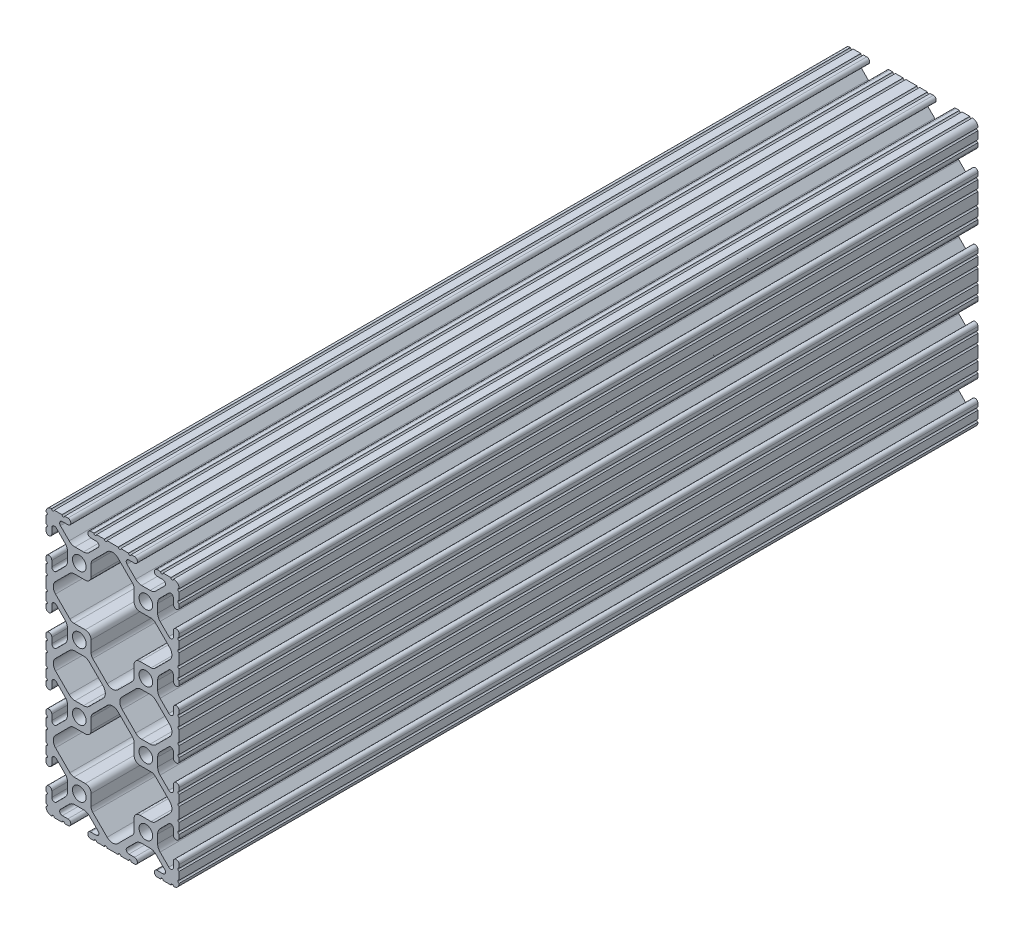
SolidWorks part; units mm, degrees
ref_plane "Front Plane" through (0, 0, 0) normal (0, 0, 1) x (1, 0, 0)
ref_plane "Top Plane" through (0, 0, 0) normal (0, 1, 0) x (1, 0, 0)
ref_plane "Right Plane" through (0, 0, 0) normal (1, 0, 0) x (0, 0, -1)
sketch "Sketch1" plane through (0, 0, 0) normal (0, 0, 1) x (1, 0, 0)
  line L0 (2.286, 55.2958) -> (-2.0184, 55.2958)
  line L1 (-3.5809, 55.943) -> (-9.0725, 61.4345)
  line L2 (-9.0725, 65.5655) -> (-3.5809, 71.057)
  line L3 (-2.0184, 71.7042) -> (2.286, 71.7042)
  line L4 (4.4958, 73.914) -> (4.4958, 78.2184)
  line L5 (5.143, 79.7809) -> (10.6345, 85.2725)
  line L6 (14.7655, 85.2725) -> (20.257, 79.7809)
  line L7 (20.9042, 78.2184) -> (20.9042, 73.914)
  line L8 (23.114, 71.7042) -> (27.4184, 71.7042)
  line L9 (28.9809, 71.057) -> (34.4725, 65.5655)
  line L10 (34.4725, 61.4345) -> (28.9809, 55.943)
  line L11 (27.4184, 55.2958) -> (23.114, 55.2958)
  line L12 (20.9042, 53.086) -> (20.9042, 48.7816)
  line L13 (20.257, 47.2191) -> (14.7655, 41.7275)
  line L14 (10.6345, 41.7275) -> (5.143, 47.2191)
  line L15 (4.4958, 48.7816) -> (4.4958, 53.086)
  line L16 (4.4958, 23.114) -> (4.4958, 27.4184)
  line L17 (5.143, 28.9809) -> (10.6345, 34.4725)
  line L18 (14.7655, 34.4725) -> (20.257, 28.9809)
  line L19 (20.9042, 27.4184) -> (20.9042, 23.114)
  line L20 (23.114, 20.9042) -> (27.4184, 20.9042)
  line L21 (28.9809, 20.257) -> (34.4725, 14.7655)
  line L22 (34.4725, 10.6345) -> (28.9809, 5.143)
  line L23 (27.4184, 4.4958) -> (23.114, 4.4958)
  line L24 (20.9042, 2.286) -> (20.9042, -2.0184)
  line L25 (20.257, -3.5809) -> (14.7655, -9.0725)
  line L26 (10.6345, -9.0725) -> (5.143, -3.5809)
  line L27 (4.4958, -2.0184) -> (4.4958, 2.286)
  line L28 (2.286, 4.4958) -> (-2.0184, 4.4958)
  line L29 (-3.5809, 5.143) -> (-9.0725, 10.6345)
  line L30 (-9.0725, 14.7655) -> (-3.5809, 20.257)
  line L31 (-2.0184, 20.9042) -> (2.286, 20.9042)
  line L32 (27.0186, 29.8958) -> (23.7824, 29.8958)
  line L33 (21.5373, 30.8258) -> (16.3286, 36.0346)
  line L34 (16.3286, 40.1654) -> (21.5373, 45.3742)
  line L35 (23.7824, 46.3042) -> (27.0186, 46.3042)
  line L36 (29.2636, 45.3743) -> (34.4725, 40.1655)
  line L37 (34.4725, 36.0345) -> (29.2636, 30.8257)
  line L38 (1.6176, 29.8958) -> (-1.6186, 29.8958)
  line L39 (-3.8636, 30.8257) -> (-9.0725, 36.0345)
  line L40 (-9.0725, 40.1655) -> (-3.8636, 45.3743)
  line L41 (-1.6186, 46.3042) -> (1.6176, 46.3042)
  line L42 (3.8627, 45.3742) -> (9.0714, 40.1654)
  line L43 (9.0714, 36.0346) -> (3.8627, 30.8258)
  line L44 (-12.7, 40.2336) -> (-12.7, 35.9664)
  line L45 (-12.7, 34.9504) -> (-12.7, 32.004)
  line L46 (-12.7, 30.988) -> (-12.7, 29.7434)
  line L47 (-10.4902, 29.7434) -> (-10.4902, 31.8743)
  line L48 (-8.7558, 32.5927) -> (-5.4258, 29.2627)
  line L49 (-4.4958, 27.0176) -> (-4.4958, 23.7824)
  line L50 (-5.4258, 21.5373) -> (-8.7558, 18.2073)
  line L51 (-10.4902, 18.9257) -> (-10.4902, 21.0566)
  line L52 (-12.7, 21.0566) -> (-12.7, 19.812)
  line L53 (-12.7, 18.796) -> (-12.7, 15.8496)
  line L54 (-12.7, 14.8336) -> (-12.7, 10.5664)
  line L55 (-12.7, 9.5504) -> (-12.7, 6.604)
  line L56 (-12.7, 5.588) -> (-12.7, 4.3434)
  line L57 (-10.4902, 4.3434) -> (-10.4902, 6.4743)
  line L58 (-8.7558, 7.1927) -> (-5.4258, 3.8627)
  line L59 (-4.4958, 1.6176) -> (-4.4958, -1.6176)
  line L60 (-5.4258, -3.8627) -> (-8.7558, -7.1927)
  line L61 (-10.4902, -6.4743) -> (-10.4902, -4.3434)
  line L62 (-12.7, -4.3434) -> (-12.7, -5.588)
  line L63 (-12.7, -6.604) -> (-12.7, -9.5504)
  line L64 (-9.5504, -12.7) -> (-6.604, -12.7)
  line L65 (-5.588, -12.7) -> (-4.3434, -12.7)
  line L66 (-4.3434, -10.4902) -> (-6.4743, -10.4902)
  line L67 (-7.1927, -8.7558) -> (-3.8627, -5.4258)
  line L68 (-1.6176, -4.4958) -> (1.6176, -4.4958)
  line L69 (3.8627, -5.4258) -> (7.1927, -8.7558)
  line L70 (6.4743, -10.4902) -> (4.3434, -10.4902)
  line L71 (4.3434, -12.7) -> (5.588, -12.7)
  line L72 (6.604, -12.7) -> (9.5504, -12.7)
  line L73 (10.5664, -12.7) -> (14.8336, -12.7)
  line L74 (15.8496, -12.7) -> (18.796, -12.7)
  line L75 (19.812, -12.7) -> (21.0566, -12.7)
  line L76 (21.0566, -10.4902) -> (18.9257, -10.4902)
  line L77 (18.2073, -8.7558) -> (21.5373, -5.4258)
  line L78 (23.7824, -4.4958) -> (27.0176, -4.4958)
  line L79 (29.2627, -5.4258) -> (32.5927, -8.7558)
  line L80 (31.8743, -10.4902) -> (29.7434, -10.4902)
  line L81 (29.7434, -12.7) -> (30.988, -12.7)
  line L82 (32.004, -12.7) -> (34.9504, -12.7)
  line L83 (38.1, -9.5504) -> (38.1, -6.604)
  line L84 (38.1, -5.588) -> (38.1, -4.3434)
  line L85 (35.8902, -4.3434) -> (35.8902, -6.4743)
  line L86 (34.1558, -7.1927) -> (30.8258, -3.8627)
  line L87 (29.8958, -1.6176) -> (29.8958, 1.6176)
  line L88 (30.8258, 3.8627) -> (34.1558, 7.1927)
  line L89 (35.8902, 6.4743) -> (35.8902, 4.3434)
  line L90 (38.1, 4.3434) -> (38.1, 5.588)
  line L91 (38.1, 6.604) -> (38.1, 9.5504)
  line L92 (38.1, 10.5664) -> (38.1, 14.8336)
  line L93 (38.1, 15.8496) -> (38.1, 18.796)
  line L94 (38.1, 19.812) -> (38.1, 21.0566)
  line L95 (35.8902, 21.0566) -> (35.8902, 18.9257)
  line L96 (34.1558, 18.2073) -> (30.8258, 21.5373)
  line L97 (29.8958, 23.7824) -> (29.8958, 27.0176)
  line L98 (30.8258, 29.2627) -> (34.1558, 32.5927)
  line L99 (35.8902, 31.8743) -> (35.8902, 29.7434)
  line L100 (38.1, 29.7434) -> (38.1, 30.988)
  line L101 (38.1, 32.004) -> (38.1, 34.9504)
  line L102 (38.1, 35.9664) -> (38.1, 40.2336)
  line L103 (38.1, 41.2496) -> (38.1, 44.196)
  line L104 (38.1, 45.212) -> (38.1, 46.4566)
  line L105 (35.8902, 46.4566) -> (35.8902, 44.3257)
  line L106 (34.1558, 43.6073) -> (30.8258, 46.9373)
  line L107 (29.8958, 49.1824) -> (29.8958, 52.4176)
  line L108 (30.8258, 54.6627) -> (34.1558, 57.9927)
  line L109 (35.8902, 57.2743) -> (35.8902, 55.1434)
  line L110 (38.1, 55.1434) -> (38.1, 56.388)
  line L111 (38.1, 57.404) -> (38.1, 60.3504)
  line L112 (38.1, 61.3664) -> (38.1, 65.6336)
  line L113 (38.1, 66.6496) -> (38.1, 69.596)
  line L114 (38.1, 70.612) -> (38.1, 71.8566)
  line L115 (35.8902, 71.8566) -> (35.8902, 69.7257)
  line L116 (34.1558, 69.0073) -> (30.8258, 72.3373)
  line L117 (29.8958, 74.5824) -> (29.8958, 77.8176)
  line L118 (30.8258, 80.0627) -> (34.1558, 83.3927)
  line L119 (35.8902, 82.6743) -> (35.8902, 80.5434)
  line L120 (38.1, 80.5434) -> (38.1, 81.788)
  line L121 (38.1, 82.804) -> (38.1, 85.7504)
  line L122 (34.9504, 88.9) -> (32.004, 88.9)
  line L123 (30.988, 88.9) -> (29.7434, 88.9)
  line L124 (29.7434, 86.6902) -> (31.8743, 86.6902)
  line L125 (32.5927, 84.9558) -> (29.2627, 81.6258)
  line L126 (27.0176, 80.6958) -> (23.7824, 80.6958)
  line L127 (21.5373, 81.6258) -> (18.2073, 84.9558)
  line L128 (18.9257, 86.6902) -> (21.0566, 86.6902)
  line L129 (21.0566, 88.9) -> (19.812, 88.9)
  line L130 (18.796, 88.9) -> (15.8496, 88.9)
  line L131 (14.8336, 88.9) -> (10.5664, 88.9)
  line L132 (9.5504, 88.9) -> (6.604, 88.9)
  line L133 (5.588, 88.9) -> (4.3434, 88.9)
  line L134 (4.3434, 86.6902) -> (6.4743, 86.6902)
  line L135 (7.1927, 84.9558) -> (3.8627, 81.6258)
  line L136 (1.6176, 80.6958) -> (-1.6176, 80.6958)
  line L137 (-3.8627, 81.6258) -> (-7.1927, 84.9558)
  line L138 (-6.4743, 86.6902) -> (-4.3434, 86.6902)
  line L139 (-4.3434, 88.9) -> (-5.588, 88.9)
  line L140 (-6.604, 88.9) -> (-9.5504, 88.9)
  line L141 (-12.7, 85.7504) -> (-12.7, 82.804)
  line L142 (-12.7, 81.788) -> (-12.7, 80.5434)
  line L143 (-10.4902, 80.5434) -> (-10.4902, 82.6743)
  line L144 (-8.7558, 83.3927) -> (-5.4258, 80.0627)
  line L145 (-4.4958, 77.8176) -> (-4.4958, 74.5824)
  line L146 (-5.4258, 72.3373) -> (-8.7558, 69.0073)
  line L147 (-10.4902, 69.7257) -> (-10.4902, 71.8566)
  line L148 (-12.7, 71.8566) -> (-12.7, 70.612)
  line L149 (-12.7, 69.596) -> (-12.7, 66.6496)
  line L150 (-12.7, 65.6336) -> (-12.7, 61.3664)
  line L151 (-12.7, 60.3504) -> (-12.7, 57.404)
  line L152 (-12.7, 56.388) -> (-12.7, 55.1434)
  line L153 (-10.4902, 55.1434) -> (-10.4902, 57.2743)
  line L154 (-8.7558, 57.9927) -> (-5.4258, 54.6627)
  line L155 (-4.4958, 52.4176) -> (-4.4958, 49.1824)
  line L156 (-5.4258, 46.9373) -> (-8.7558, 43.6073)
  line L157 (-10.4902, 44.3257) -> (-10.4902, 46.4566)
  line L158 (-12.7, 46.4566) -> (-12.7, 45.212)
  line L159 (-12.7, 44.196) -> (-12.7, 41.2496)
  arc A0 (4.4958, 53.086) -> (2.286, 55.2958) centre (2.286, 53.086) ccw
  arc A1 (-3.5809, 55.943) -> (-2.0184, 55.2958) centre (-2.0184, 57.5056) ccw
  arc A2 (-9.0725, 65.5655) -> (-9.0725, 61.4345) centre (-7.0071, 63.5) ccw
  arc A3 (-2.0184, 71.7042) -> (-3.5809, 71.057) centre (-2.0184, 69.4944) ccw
  arc A4 (2.286, 71.7042) -> (4.4958, 73.914) centre (2.286, 73.914) ccw
  arc A5 (5.143, 79.7809) -> (4.4958, 78.2184) centre (6.7056, 78.2184) ccw
  arc A6 (14.7655, 85.2725) -> (10.6345, 85.2725) centre (12.7, 83.2071) ccw
  arc A7 (20.9042, 78.2184) -> (20.257, 79.7809) centre (18.6944, 78.2184) ccw
  arc A8 (20.9042, 73.914) -> (23.114, 71.7042) centre (23.114, 73.914) ccw
  arc A9 (28.9809, 71.057) -> (27.4184, 71.7042) centre (27.4184, 69.4944) ccw
  arc A10 (34.4725, 61.4345) -> (34.4725, 65.5655) centre (32.4071, 63.5) ccw
  arc A11 (27.4184, 55.2958) -> (28.9809, 55.943) centre (27.4184, 57.5056) ccw
  arc A12 (23.114, 55.2958) -> (20.9042, 53.086) centre (23.114, 53.086) ccw
  arc A13 (20.257, 47.2191) -> (20.9042, 48.7816) centre (18.6944, 48.7816) ccw
  arc A14 (10.6345, 41.7275) -> (14.7655, 41.7275) centre (12.7, 43.7929) ccw
  arc A15 (4.4958, 48.7816) -> (5.143, 47.2191) centre (6.7056, 48.7816) ccw
  arc A16 (2.286, 20.9042) -> (4.4958, 23.114) centre (2.286, 23.114) ccw
  arc A17 (5.143, 28.9809) -> (4.4958, 27.4184) centre (6.7056, 27.4184) ccw
  arc A18 (14.7655, 34.4725) -> (10.6345, 34.4725) centre (12.7, 32.4071) ccw
  arc A19 (20.9042, 27.4184) -> (20.257, 28.9809) centre (18.6944, 27.4184) ccw
  arc A20 (20.9042, 23.114) -> (23.114, 20.9042) centre (23.114, 23.114) ccw
  arc A21 (28.9809, 20.257) -> (27.4184, 20.9042) centre (27.4184, 18.6944) ccw
  arc A22 (34.4725, 10.6345) -> (34.4725, 14.7655) centre (32.4071, 12.7) ccw
  arc A23 (27.4184, 4.4958) -> (28.9809, 5.143) centre (27.4184, 6.7056) ccw
  arc A24 (23.114, 4.4958) -> (20.9042, 2.286) centre (23.114, 2.286) ccw
  arc A25 (20.257, -3.5809) -> (20.9042, -2.0184) centre (18.6944, -2.0184) ccw
  arc A26 (10.6345, -9.0725) -> (14.7655, -9.0725) centre (12.7, -7.0071) ccw
  arc A27 (4.4958, -2.0184) -> (5.143, -3.5809) centre (6.7056, -2.0184) ccw
  arc A28 (4.4958, 2.286) -> (2.286, 4.4958) centre (2.286, 2.286) ccw
  arc A29 (-3.5809, 5.143) -> (-2.0184, 4.4958) centre (-2.0184, 6.7056) ccw
  arc A30 (-9.0725, 14.7655) -> (-9.0725, 10.6345) centre (-7.0071, 12.7) ccw
  arc A31 (-2.0184, 20.9042) -> (-3.5809, 20.257) centre (-2.0184, 18.6944) ccw
  arc A32 (27.0186, 29.8958) -> (29.2636, 30.8257) centre (27.0186, 33.0708) ccw
  arc A33 (21.5373, 30.8258) -> (23.7824, 29.8958) centre (23.7824, 33.0708) ccw
  arc A34 (16.3286, 40.1654) -> (16.3286, 36.0346) centre (18.3941, 38.1) ccw
  arc A35 (23.7824, 46.3042) -> (21.5373, 45.3742) centre (23.7824, 43.1292) ccw
  arc A36 (29.2636, 45.3743) -> (27.0186, 46.3042) centre (27.0186, 43.1292) ccw
  arc A37 (34.4725, 36.0345) -> (34.4725, 40.1655) centre (32.4071, 38.1) ccw
  arc A38 (1.6176, 29.8958) -> (3.8627, 30.8258) centre (1.6176, 33.0708) ccw
  arc A39 (-3.8636, 30.8257) -> (-1.6186, 29.8958) centre (-1.6186, 33.0708) ccw
  arc A40 (-9.0725, 40.1655) -> (-9.0725, 36.0345) centre (-7.0071, 38.1) ccw
  arc A41 (-1.6186, 46.3042) -> (-3.8636, 45.3743) centre (-1.6186, 43.1292) ccw
  arc A42 (3.8627, 45.3742) -> (1.6176, 46.3042) centre (1.6176, 43.1292) ccw
  arc A43 (9.0714, 36.0346) -> (9.0714, 40.1654) centre (7.0059, 38.1) ccw
  circle A44 centre (25.4, 76.2) radius 2.6035
  circle A45 centre (0, 76.2) radius 2.6035
  circle A46 centre (25.4, 50.8) radius 2.6035
  circle A47 centre (0, 50.8) radius 2.6035
  circle A48 centre (25.4, 0) radius 2.6035
  circle A49 centre (0, 0) radius 2.6035
  circle A50 centre (25.4, 25.4) radius 2.6035
  circle A51 centre (0, 25.4) radius 2.6035
  arc A52 (-12.7, 34.9504) -> (-12.7, 35.9664) centre (-12.7, 35.4584) ccw
  arc A53 (-12.7, 30.988) -> (-12.7, 32.004) centre (-12.7, 31.496) ccw
  arc A54 (-12.7, 29.7434) -> (-10.4902, 29.7434) centre (-11.5951, 29.7434) ccw
  arc A55 (-8.7558, 32.5927) -> (-10.4902, 31.8743) centre (-9.4742, 31.8743) ccw
  arc A56 (-4.4958, 27.0176) -> (-5.4258, 29.2627) centre (-7.6708, 27.0176) ccw
  arc A57 (-5.4258, 21.5373) -> (-4.4958, 23.7824) centre (-7.6708, 23.7824) ccw
  arc A58 (-10.4902, 18.9257) -> (-8.7558, 18.2073) centre (-9.4742, 18.9257) ccw
  arc A59 (-10.4902, 21.0566) -> (-12.7, 21.0566) centre (-11.5951, 21.0566) ccw
  arc A60 (-12.7, 18.796) -> (-12.7, 19.812) centre (-12.7, 19.304) ccw
  arc A61 (-12.7, 14.8336) -> (-12.7, 15.8496) centre (-12.7, 15.3416) ccw
  arc A62 (-12.7, 9.5504) -> (-12.7, 10.5664) centre (-12.7, 10.0584) ccw
  arc A63 (-12.7, 5.588) -> (-12.7, 6.604) centre (-12.7, 6.096) ccw
  arc A64 (-12.7, 4.3434) -> (-10.4902, 4.3434) centre (-11.5951, 4.3434) ccw
  arc A65 (-8.7558, 7.1927) -> (-10.4902, 6.4743) centre (-9.4742, 6.4743) ccw
  arc A66 (-4.4958, 1.6176) -> (-5.4258, 3.8627) centre (-7.6708, 1.6176) ccw
  arc A67 (-5.4258, -3.8627) -> (-4.4958, -1.6176) centre (-7.6708, -1.6176) ccw
  arc A68 (-10.4902, -6.4743) -> (-8.7558, -7.1927) centre (-9.4742, -6.4743) ccw
  arc A69 (-10.4902, -4.3434) -> (-12.7, -4.3434) centre (-11.5951, -4.3434) ccw
  arc A70 (-12.7, -6.604) -> (-12.7, -5.588) centre (-12.7, -6.096) ccw
  arc A71 (-12.6998, -10.5664) -> (-12.7, -9.5504) centre (-12.7, -10.0584) ccw
  arc A72 (-12.6998, -10.5664) -> (-10.5664, -12.6998) centre (-10.5918, -10.5918) ccw
  arc A73 (-9.5504, -12.7) -> (-10.5664, -12.6998) centre (-10.0584, -12.7) ccw
  arc A74 (-5.588, -12.7) -> (-6.604, -12.7) centre (-6.096, -12.7) ccw
  arc A75 (-4.3434, -12.7) -> (-4.3434, -10.4902) centre (-4.3434, -11.5951) ccw
  arc A76 (-7.1927, -8.7558) -> (-6.4743, -10.4902) centre (-6.4743, -9.4742) ccw
  arc A77 (-1.6176, -4.4958) -> (-3.8627, -5.4258) centre (-1.6176, -7.6708) ccw
  arc A78 (3.8627, -5.4258) -> (1.6176, -4.4958) centre (1.6176, -7.6708) ccw
  arc A79 (6.4743, -10.4902) -> (7.1927, -8.7558) centre (6.4743, -9.4742) ccw
  arc A80 (4.3434, -10.4902) -> (4.3434, -12.7) centre (4.3434, -11.5951) ccw
  arc A81 (6.604, -12.7) -> (5.588, -12.7) centre (6.096, -12.7) ccw
  arc A82 (10.5664, -12.7) -> (9.5504, -12.7) centre (10.0584, -12.7) ccw
  arc A83 (15.8496, -12.7) -> (14.8336, -12.7) centre (15.3416, -12.7) ccw
  arc A84 (19.812, -12.7) -> (18.796, -12.7) centre (19.304, -12.7) ccw
  arc A85 (21.0566, -12.7) -> (21.0566, -10.4902) centre (21.0566, -11.5951) ccw
  arc A86 (18.2073, -8.7558) -> (18.9257, -10.4902) centre (18.9257, -9.4742) ccw
  arc A87 (23.7824, -4.4958) -> (21.5373, -5.4258) centre (23.7824, -7.6708) ccw
  arc A88 (29.2627, -5.4258) -> (27.0176, -4.4958) centre (27.0176, -7.6708) ccw
  arc A89 (31.8743, -10.4902) -> (32.5927, -8.7558) centre (31.8743, -9.4742) ccw
  arc A90 (29.7434, -10.4902) -> (29.7434, -12.7) centre (29.7434, -11.5951) ccw
  arc A91 (32.004, -12.7) -> (30.988, -12.7) centre (31.496, -12.7) ccw
  arc A92 (35.9664, -12.6998) -> (34.9504, -12.7) centre (35.4584, -12.7) ccw
  arc A93 (35.9664, -12.6998) -> (38.0998, -10.5664) centre (35.9918, -10.5918) ccw
  arc A94 (38.1, -9.5504) -> (38.0998, -10.5664) centre (38.1, -10.0584) ccw
  arc A95 (38.1, -5.588) -> (38.1, -6.604) centre (38.1, -6.096) ccw
  arc A96 (38.1, -4.3434) -> (35.8902, -4.3434) centre (36.9951, -4.3434) ccw
  arc A97 (34.1558, -7.1927) -> (35.8902, -6.4743) centre (34.8742, -6.4743) ccw
  arc A98 (29.8958, -1.6176) -> (30.8258, -3.8627) centre (33.0708, -1.6176) ccw
  arc A99 (30.8258, 3.8627) -> (29.8958, 1.6176) centre (33.0708, 1.6176) ccw
  arc A100 (35.8902, 6.4743) -> (34.1558, 7.1927) centre (34.8742, 6.4743) ccw
  arc A101 (35.8902, 4.3434) -> (38.1, 4.3434) centre (36.9951, 4.3434) ccw
  arc A102 (38.1, 6.604) -> (38.1, 5.588) centre (38.1, 6.096) ccw
  arc A103 (38.1, 10.5664) -> (38.1, 9.5504) centre (38.1, 10.0584) ccw
  arc A104 (38.1, 15.8496) -> (38.1, 14.8336) centre (38.1, 15.3416) ccw
  arc A105 (38.1, 19.812) -> (38.1, 18.796) centre (38.1, 19.304) ccw
  arc A106 (38.1, 21.0566) -> (35.8902, 21.0566) centre (36.9951, 21.0566) ccw
  arc A107 (34.1558, 18.2073) -> (35.8902, 18.9257) centre (34.8742, 18.9257) ccw
  arc A108 (29.8958, 23.7824) -> (30.8258, 21.5373) centre (33.0708, 23.7824) ccw
  arc A109 (30.8258, 29.2627) -> (29.8958, 27.0176) centre (33.0708, 27.0176) ccw
  arc A110 (35.8902, 31.8743) -> (34.1558, 32.5927) centre (34.8742, 31.8743) ccw
  arc A111 (35.8902, 29.7434) -> (38.1, 29.7434) centre (36.9951, 29.7434) ccw
  arc A112 (38.1, 32.004) -> (38.1, 30.988) centre (38.1, 31.496) ccw
  arc A113 (38.1, 35.9664) -> (38.1, 34.9504) centre (38.1, 35.4584) ccw
  arc A114 (38.1, 41.2496) -> (38.1, 40.2336) centre (38.1, 40.7416) ccw
  arc A115 (38.1, 45.212) -> (38.1, 44.196) centre (38.1, 44.704) ccw
  arc A116 (38.1, 46.4566) -> (35.8902, 46.4566) centre (36.9951, 46.4566) ccw
  arc A117 (34.1558, 43.6073) -> (35.8902, 44.3257) centre (34.8742, 44.3257) ccw
  arc A118 (29.8958, 49.1824) -> (30.8258, 46.9373) centre (33.0708, 49.1824) ccw
  arc A119 (30.8258, 54.6627) -> (29.8958, 52.4176) centre (33.0708, 52.4176) ccw
  arc A120 (35.8902, 57.2743) -> (34.1558, 57.9927) centre (34.8742, 57.2743) ccw
  arc A121 (35.8902, 55.1434) -> (38.1, 55.1434) centre (36.9951, 55.1434) ccw
  arc A122 (38.1, 57.404) -> (38.1, 56.388) centre (38.1, 56.896) ccw
  arc A123 (38.1, 61.3664) -> (38.1, 60.3504) centre (38.1, 60.8584) ccw
  arc A124 (38.1, 66.6496) -> (38.1, 65.6336) centre (38.1, 66.1416) ccw
  arc A125 (38.1, 70.612) -> (38.1, 69.596) centre (38.1, 70.104) ccw
  arc A126 (38.1, 71.8566) -> (35.8902, 71.8566) centre (36.9951, 71.8566) ccw
  arc A127 (34.1558, 69.0073) -> (35.8902, 69.7257) centre (34.8742, 69.7257) ccw
  arc A128 (29.8958, 74.5824) -> (30.8258, 72.3373) centre (33.0708, 74.5824) ccw
  arc A129 (30.8258, 80.0627) -> (29.8958, 77.8176) centre (33.0708, 77.8176) ccw
  arc A130 (35.8902, 82.6743) -> (34.1558, 83.3927) centre (34.8742, 82.6743) ccw
  arc A131 (35.8902, 80.5434) -> (38.1, 80.5434) centre (36.9951, 80.5434) ccw
  arc A132 (38.1, 82.804) -> (38.1, 81.788) centre (38.1, 82.296) ccw
  arc A133 (38.0998, 86.7664) -> (38.1, 85.7504) centre (38.1, 86.2584) ccw
  arc A134 (38.0998, 86.7664) -> (35.9664, 88.8998) centre (35.9918, 86.7918) ccw
  arc A135 (34.9504, 88.9) -> (35.9664, 88.8998) centre (35.4584, 88.9) ccw
  arc A136 (30.988, 88.9) -> (32.004, 88.9) centre (31.496, 88.9) ccw
  arc A137 (29.7434, 88.9) -> (29.7434, 86.6902) centre (29.7434, 87.7951) ccw
  arc A138 (32.5927, 84.9558) -> (31.8743, 86.6902) centre (31.8743, 85.6742) ccw
  arc A139 (27.0176, 80.6958) -> (29.2627, 81.6258) centre (27.0176, 83.8708) ccw
  arc A140 (21.5373, 81.6258) -> (23.7824, 80.6958) centre (23.7824, 83.8708) ccw
  arc A141 (18.9257, 86.6902) -> (18.2073, 84.9558) centre (18.9257, 85.6742) ccw
  arc A142 (21.0566, 86.6902) -> (21.0566, 88.9) centre (21.0566, 87.7951) ccw
  arc A143 (18.796, 88.9) -> (19.812, 88.9) centre (19.304, 88.9) ccw
  arc A144 (14.8336, 88.9) -> (15.8496, 88.9) centre (15.3416, 88.9) ccw
  arc A145 (9.5504, 88.9) -> (10.5664, 88.9) centre (10.0584, 88.9) ccw
  arc A146 (5.588, 88.9) -> (6.604, 88.9) centre (6.096, 88.9) ccw
  arc A147 (4.3434, 88.9) -> (4.3434, 86.6902) centre (4.3434, 87.7951) ccw
  arc A148 (7.1927, 84.9558) -> (6.4743, 86.6902) centre (6.4743, 85.6742) ccw
  arc A149 (1.6176, 80.6958) -> (3.8627, 81.6258) centre (1.6176, 83.8708) ccw
  arc A150 (-3.8627, 81.6258) -> (-1.6176, 80.6958) centre (-1.6176, 83.8708) ccw
  arc A151 (-6.4743, 86.6902) -> (-7.1927, 84.9558) centre (-6.4743, 85.6742) ccw
  arc A152 (-4.3434, 86.6902) -> (-4.3434, 88.9) centre (-4.3434, 87.7951) ccw
  arc A153 (-6.604, 88.9) -> (-5.588, 88.9) centre (-6.096, 88.9) ccw
  arc A154 (-10.5664, 88.8998) -> (-9.5504, 88.9) centre (-10.0584, 88.9) ccw
  arc A155 (-10.5664, 88.8998) -> (-12.6998, 86.7664) centre (-10.5918, 86.7918) ccw
  arc A156 (-12.7, 85.7504) -> (-12.6998, 86.7664) centre (-12.7, 86.2584) ccw
  arc A157 (-12.7, 81.788) -> (-12.7, 82.804) centre (-12.7, 82.296) ccw
  arc A158 (-12.7, 80.5434) -> (-10.4902, 80.5434) centre (-11.5951, 80.5434) ccw
  arc A159 (-8.7558, 83.3927) -> (-10.4902, 82.6743) centre (-9.4742, 82.6743) ccw
  arc A160 (-4.4958, 77.8176) -> (-5.4258, 80.0627) centre (-7.6708, 77.8176) ccw
  arc A161 (-5.4258, 72.3373) -> (-4.4958, 74.5824) centre (-7.6708, 74.5824) ccw
  arc A162 (-10.4902, 69.7257) -> (-8.7558, 69.0073) centre (-9.4742, 69.7257) ccw
  arc A163 (-10.4902, 71.8566) -> (-12.7, 71.8566) centre (-11.5951, 71.8566) ccw
  arc A164 (-12.7, 69.596) -> (-12.7, 70.612) centre (-12.7, 70.104) ccw
  arc A165 (-12.7, 65.6336) -> (-12.7, 66.6496) centre (-12.7, 66.1416) ccw
  arc A166 (-12.7, 60.3504) -> (-12.7, 61.3664) centre (-12.7, 60.8584) ccw
  arc A167 (-12.7, 56.388) -> (-12.7, 57.404) centre (-12.7, 56.896) ccw
  arc A168 (-12.7, 55.1434) -> (-10.4902, 55.1434) centre (-11.5951, 55.1434) ccw
  arc A169 (-8.7558, 57.9927) -> (-10.4902, 57.2743) centre (-9.4742, 57.2743) ccw
  arc A170 (-4.4958, 52.4176) -> (-5.4258, 54.6627) centre (-7.6708, 52.4176) ccw
  arc A171 (-5.4258, 46.9373) -> (-4.4958, 49.1824) centre (-7.6708, 49.1824) ccw
  arc A172 (-10.4902, 44.3257) -> (-8.7558, 43.6073) centre (-9.4742, 44.3257) ccw
  arc A173 (-10.4902, 46.4566) -> (-12.7, 46.4566) centre (-11.5951, 46.4566) ccw
  arc A174 (-12.7, 44.196) -> (-12.7, 45.212) centre (-12.7, 44.704) ccw
  arc A175 (-12.7, 40.2336) -> (-12.7, 41.2496) centre (-12.7, 40.7416) ccw
extrude "Extrude1" add sketch "Sketch1" against normal blind 304.8
